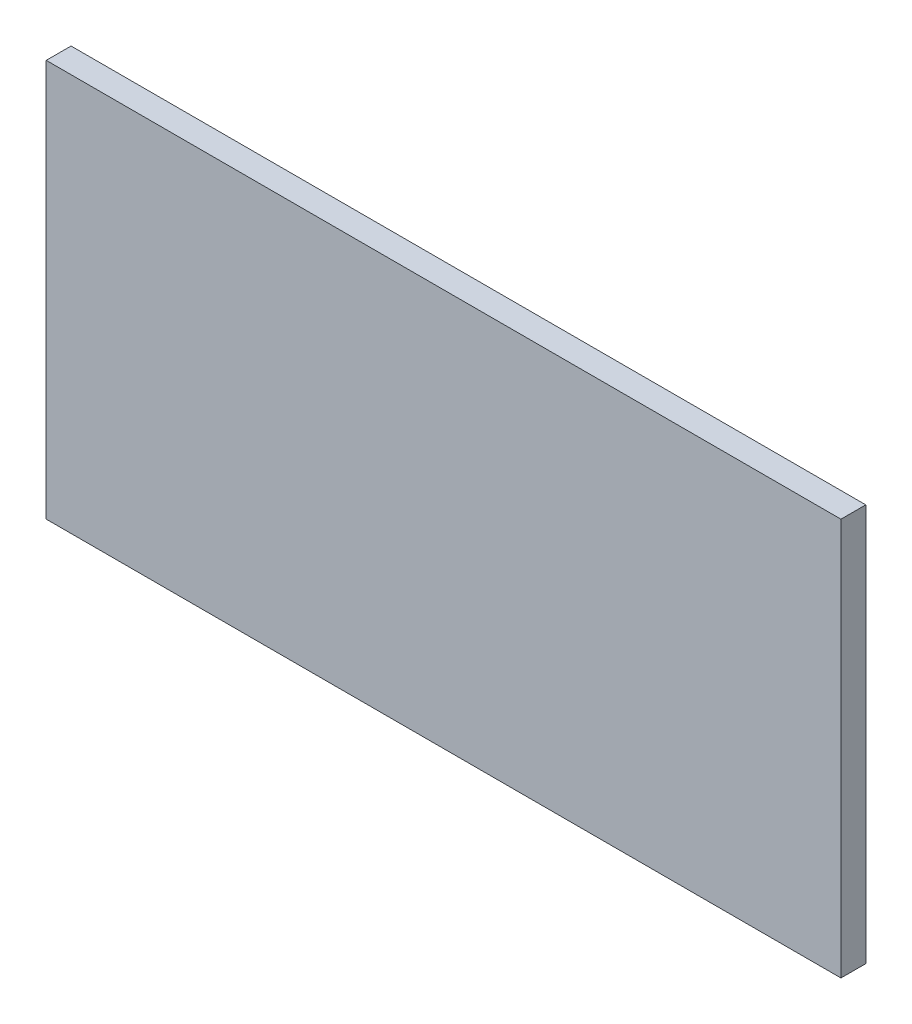
SolidWorks part; units mm, degrees
material "6061 Alloy"
ref_plane "Front Plane" through (0, 0, 0) normal (0, 0, 1) x (1, 0, 0)
ref_plane "Top Plane" through (0, 0, 0) normal (0, 1, 0) x (1, 0, 0)
ref_plane "Right Plane" through (0, 0, 0) normal (1, 0, 0) x (0, 0, -1)
sketch "Sketch1" plane through (0, 0, 0) normal (0, 0, 1) x (1, 0, 0)
  line L1 (0, 0) -> (101.6, 0)
  line L2 (0, 0) -> (0, -50.8)
  line L3 (0, -50.8) -> (101.6, -50.8)
  line L4 (101.6, 0) -> (101.6, -50.8)
  dimension "D1" = 101.6
  dimension "D2" = 50.8
extrude "Boss-Extrude1" add sketch "Sketch1" along normal blind 3.175
ref_plane "Plane1" through (50.8, 0, 0) normal (1, 0, 0) x (0, 0, -1)
